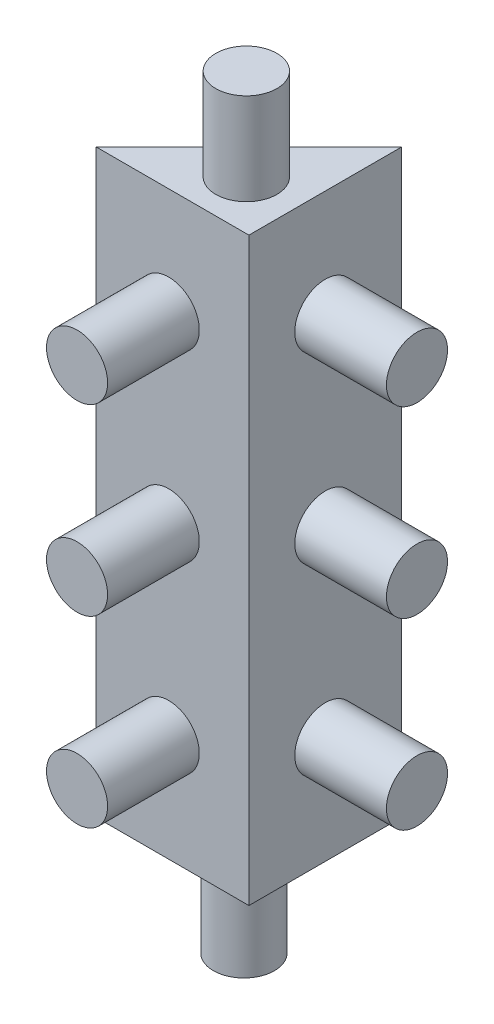
SolidWorks part; units mm, degrees
ref_plane "Front Plane" through (0, 0, 0) normal (0, 0, 1) x (1, 0, 0)
ref_plane "Top Plane" through (0, 0, 0) normal (0, 1, 0) x (1, 0, 0)
ref_plane "Right Plane" through (0, 0, 0) normal (1, 0, 0) x (0, 0, -1)
sketch "Sketch4" plane through (0, 0, 0) normal (0, 1, 0) x (1, 0, 0)
  line L0 (-6.0356, -6.0356) -> (6.6644, 6.6644)
  line L3 (-6.0356, -6.0356) -> (6.6644, -6.0356)
  line L4 (6.6644, 6.6644) -> (6.6644, -6.0356)
  line L5 (0, 0) -> (6.6644, -6.0356) construction
  line L6 (-6.0356, -6.0356) -> (6.6644, 6.6644) construction
  point P0 (0, 0)
  dimension "D1" = 12.7
  dimension "D2" = 12.7
extrude "Boss-Extrude1" add sketch "Sketch4" along normal blind 48.26
sketch "Sketch6" plane through (0, 0, 6.0356) normal (0, 0, 1) x (1, 0, 0)
  line L0 (-6.0356, 0) -> (6.6644, 0) construction
  circle A0 centre (0, 8.89) radius 2.54
  circle A1 centre (0, 24.13) radius 2.54
  circle A2 centre (0, 39.37) radius 2.54
  dimension "D1" = 5.08
  dimension "D2" = 15.24
  dimension "D3" = 15.24
  dimension "D4" = 8.89
extrude "Boss-Extrude3" add sketch "Sketch6" along normal blind 7.62
sketch "Sketch7" plane through (6.6644, 0, 0) normal (1, 0, 0) x (0, 0, -1)
  line L0 (-6.0356, 0) -> (6.6644, 0) construction
  circle A0 centre (0.3144, 8.89) radius 2.54
  circle A1 centre (0.3144, 24.13) radius 2.54
  circle A2 centre (0.3144, 39.37) radius 2.54
  dimension "D1" = 5.08
  dimension "D2" = 15.24
  dimension "D3" = 15.24
  dimension "D4" = 8.89
extrude "Boss-Extrude4" add sketch "Sketch7" along normal blind 7.62
sketch "Sketch8" plane through (0, 0, 0) normal (0, -1, 0) x (1, 0, 0)
  circle A0 centre (2.2592, 2.046) radius 2.54
  dimension "D1" = 5.08
  dimension "D2" = 3.048
extrude "Boss-Extrude5" add sketch "Sketch8" along normal blind 7.62
sketch "Sketch9" plane through (0, 48.26, 0) normal (0, 1, 0) x (1, 0, 0)
  line L0 (6.6644, 6.6644) -> (-6.0356, -6.0356) construction
  circle A0 centre (2.3604, -1.9448) radius 2.54
  point P6 (0.3144, 0.3144)
  dimension "D1" = 5.08
  dimension "D2" = 3.048
extrude "Boss-Extrude6" add sketch "Sketch9" along normal blind 7.62
sketch "Sketch10" plane through (0, -7.62, 0) normal (0, -1, 0) x (1, 0, 0)
  circle A0 centre (2.2592, 2.046) radius 2.54 construction
  circle A1 centre (2.2592, 2.046) radius 2.54
sketch "Sketch11" plane through (14.2844, 0, 0) normal (1, 0, 0) x (0, 0, -1)
  circle A0 centre (0.3144, 8.89) radius 2.54 construction
  circle A1 centre (0.3144, 24.13) radius 2.54 construction
  circle A2 centre (0.3144, 39.37) radius 2.54 construction
  circle A3 centre (0.3144, 8.89) radius 2.54
  circle A4 centre (0.3144, 24.13) radius 2.54
  circle A5 centre (0.3144, 39.37) radius 2.54
